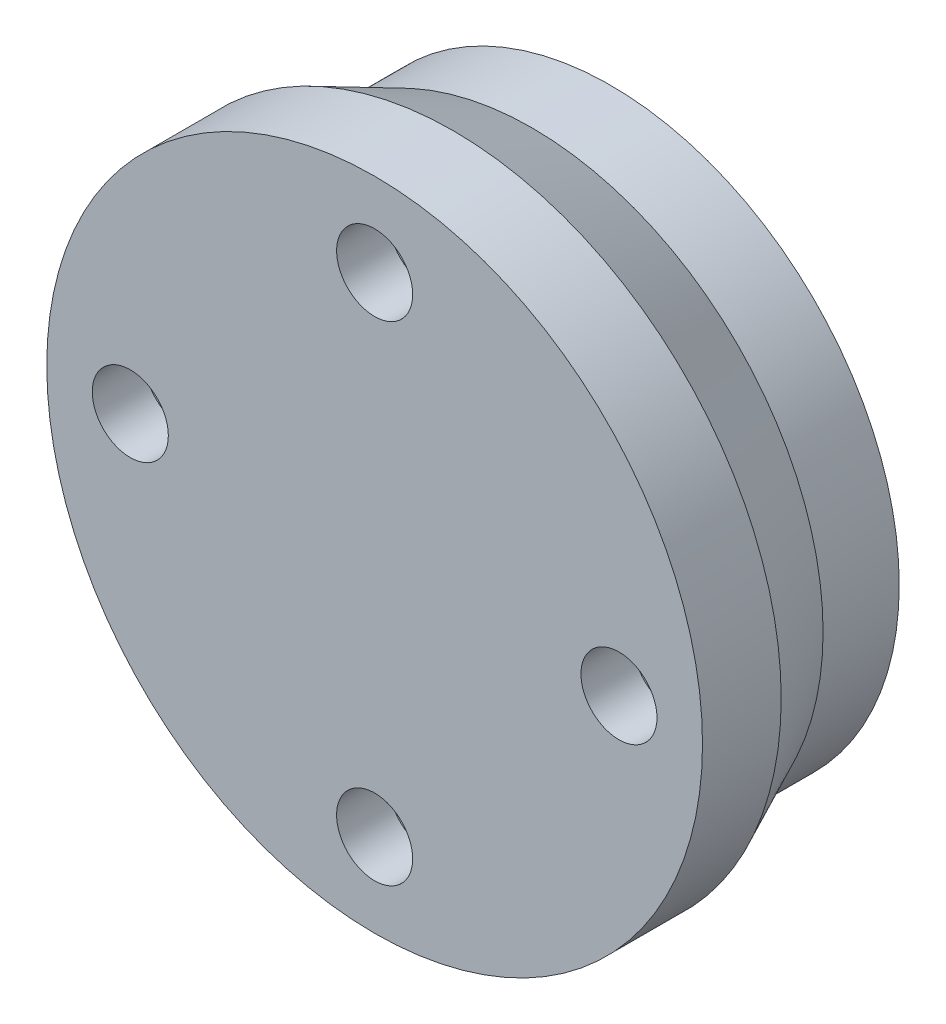
SolidWorks part; units mm, degrees
ref_plane "Front Plane" through (0, 0, 0) normal (0, 0, 1) x (1, 0, 0)
ref_plane "Top Plane" through (0, 0, 0) normal (0, 1, 0) x (1, 0, 0)
ref_plane "Right Plane" through (0, 0, 0) normal (1, 0, 0) x (0, 0, -1)
sketch "Sketch1" plane through (0, 0, 0) normal (0, 0, 1) x (1, 0, 0)
  circle A0 centre (0, 0) radius 11
  dimension "D1" = 22
extrude "Boss-Extrude1" add sketch "Sketch1" along normal mid plane 3
sketch "Sketch2" plane through (0, 0, 0) normal (1, 0, 0) x (0, 0, -1)
  line L0 (0, 0) -> (-9.3347, 0) construction
  line L1 (-4.5, 0) -> (-4.5, 12.5)
  line L3 (-1.5, 11) -> (-1.5, -11) construction
  line L4 (-1.5, 11.0965) -> (-4.5, 12.5)
  line L5 (-1.5, 11.0965) -> (-1.5, 0)
  line L6 (-1.5, 0) -> (-4.5, 0)
  dimension "D1" = 12.5
  dimension "D2" = 3
  dimension "D3" = 25.072
revolve "Revolve1" add sketch "Sketch2" angle 360 about L0
sketch "Sketch4" plane through (0, 0, 4.5) normal (0, 0, 1) x (1, 0, 0)
  circle A0 centre (0, 0) radius 12.5
  circle A1 centre (0, 0) radius 12.5 construction
extrude "Boss-Extrude2" add sketch "Sketch4" along normal blind 3
sketch "Sketch5" plane through (0, 0, 7.5) normal (0, 0, 1) x (1, 0, 0)
  circle A0 centre (0, 9.315) radius 1.45
  circle A1 centre (0, 9.315) radius 1.45 construction
  circle A2 centre (9.315, 0) radius 1.45
  circle A3 centre (0, -9.315) radius 1.45
  circle A4 centre (-9.315, 0) radius 1.45
  point P14 (0, 0)
  dimension "D1" = 0
  dimension "D2" = 4
extrude "Cut-Extrude1" cut sketch "Sketch5" against normal blind 2
sketch "Sketch6" plane through (0, 0, -1.5) normal (0, 0, -1) x (-1, 0, 0)
  circle A0 centre (0, 7.5) radius 1.5
  circle A1 centre (0, 7.5) radius 1.5 construction
  circle A2 centre (7.5, 0) radius 1.5
  circle A3 centre (0, -7.5) radius 1.5
  circle A4 centre (-7.5, 0) radius 1.5
  point P14 (0, 0)
  dimension "D1" = 4
extrude "Cut-Extrude2" cut sketch "Sketch6" against normal blind 2
